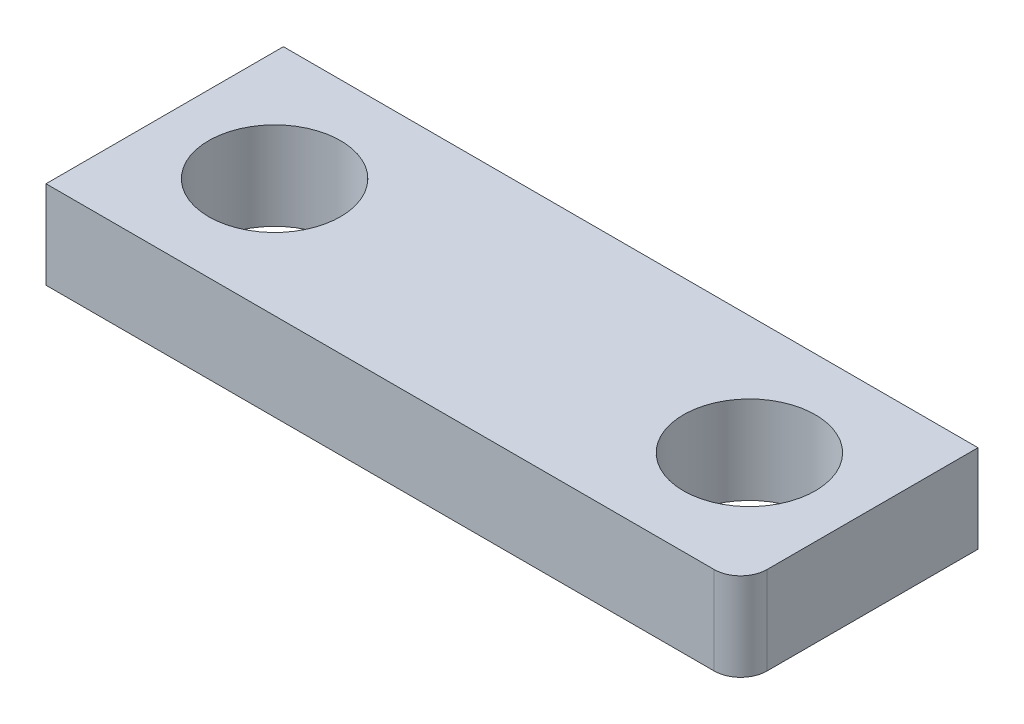
SolidWorks part; units mm, degrees
ref_plane "前视基准面" through (0, 0, 0) normal (0, 0, 1) x (1, 0, 0)
ref_plane "上视基准面" through (0, 0, 0) normal (0, 1, 0) x (1, 0, 0)
ref_plane "右视基准面" through (0, 0, 0) normal (1, 0, 0) x (0, 0, -1)
sketch "草图1" plane through (0, 0, 0) normal (0, 1, 0) x (1, 0, 0)
  line L1 (-39.5, 13.5) -> (39.5, 13.5)
  line L2 (-39.5, 13.5) -> (-39.5, -13.5)
  line L3 (-39.5, -13.5) -> (39.5, -13.5)
  line L4 (39.5, 13.5) -> (39.5, -13.5)
  line L5 (-39.5, 13.5) -> (39.5, -13.5) construction
  line L6 (-39.5, -13.5) -> (39.5, 13.5) construction
  point P0 (0, 0)
  dimension "D1" = 79
  dimension "D2" = 27
extrude "凸台-拉伸1" add sketch "草图1" along normal blind 10
sketch "草图2" plane through (0, 0, 0) normal (0, -1, 0) x (1, 0, 0)
  line L0 (-39.5, 0) -> (39.5, 0) construction
  line L1 (-39.5, -13.5) -> (-39.5, 13.5) construction
  line L2 (39.5, 13.5) -> (39.5, -13.5) construction
ref_plane "基准面1" through (0, 0, 0) normal (0, 0, 1) x (1, 0, 0)
sketch "草图3" plane through (0, 10, 0) normal (0, 1, 0) x (1, 0, 0)
  line L0 (-14.85, 0) -> (14.85, 0) construction
  line L1 (0, 13.5) -> (0, -13.5) construction
  line L2 (39.5, 13.5) -> (-39.5, 13.5) construction
  line L3 (-39.5, -13.5) -> (39.5, -13.5) construction
  circle A0 centre (-27, 0) radius 7.5
  circle A1 centre (27, 0) radius 7.5
  dimension "D1" = 15
  dimension "D2" = 54
extrude "切除-拉伸1" cut sketch "草图3" against normal through all contours A1 | A0
fillet "圆角1" radius 3 1 edges at (39.5, 5, 13.5)
